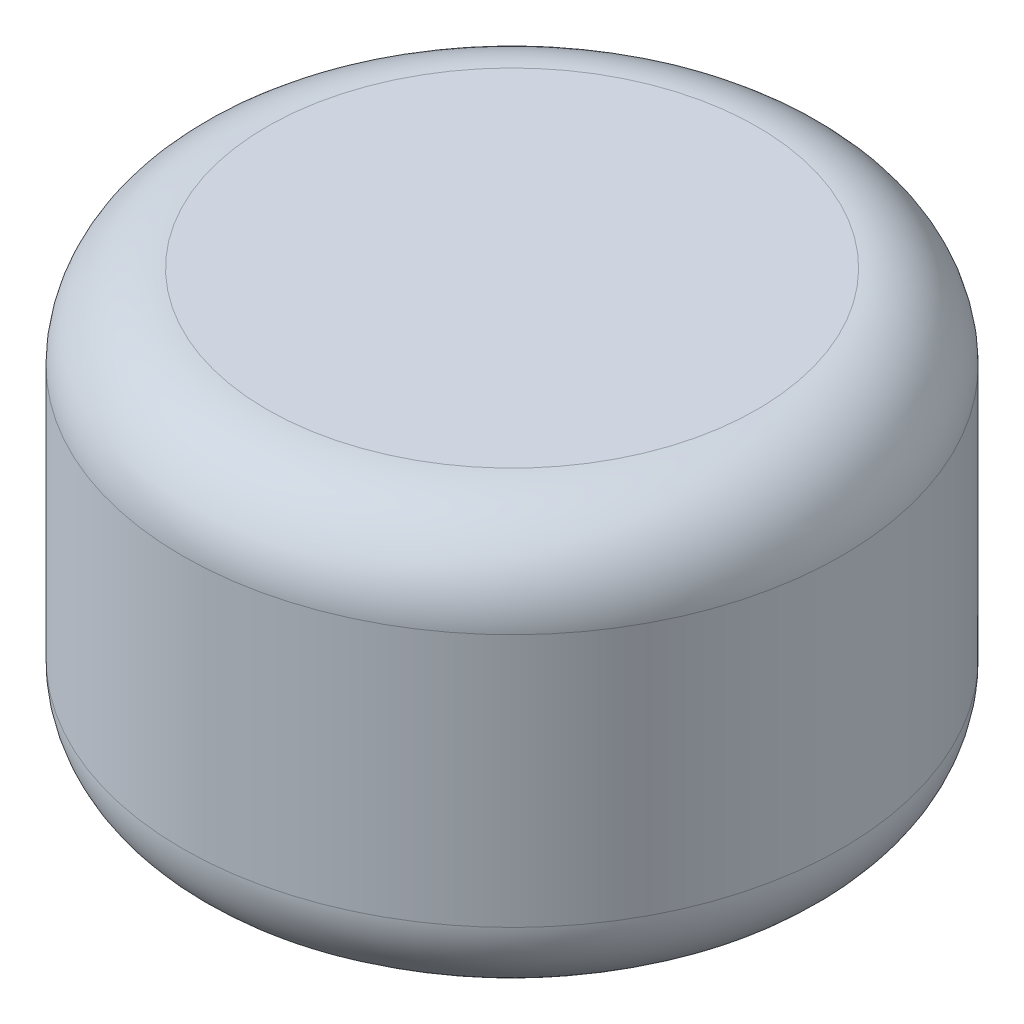
SolidWorks part; units mm, degrees
ref_plane "Front Plane" through (0, 0, 0) normal (0, 0, 1) x (1, 0, 0)
ref_plane "Top Plane" through (0, 0, 0) normal (0, 1, 0) x (1, 0, 0)
ref_plane "Right Plane" through (0, 0, 0) normal (1, 0, 0) x (0, 0, -1)
sketch "Sketch1" plane through (0, 0, 0) normal (0, 1, 0) x (1, 0, 0)
  circle A0 centre (0, 0) radius 49.53
  dimension "D1" = 99.06
extrude "Boss-Extrude1" add sketch "Sketch1" along normal blind 63.5 contours A0
fillet "Fillet1" radius 12.7 2 edges at (0, 0, 49.53) (0, 63.5, 49.53)
